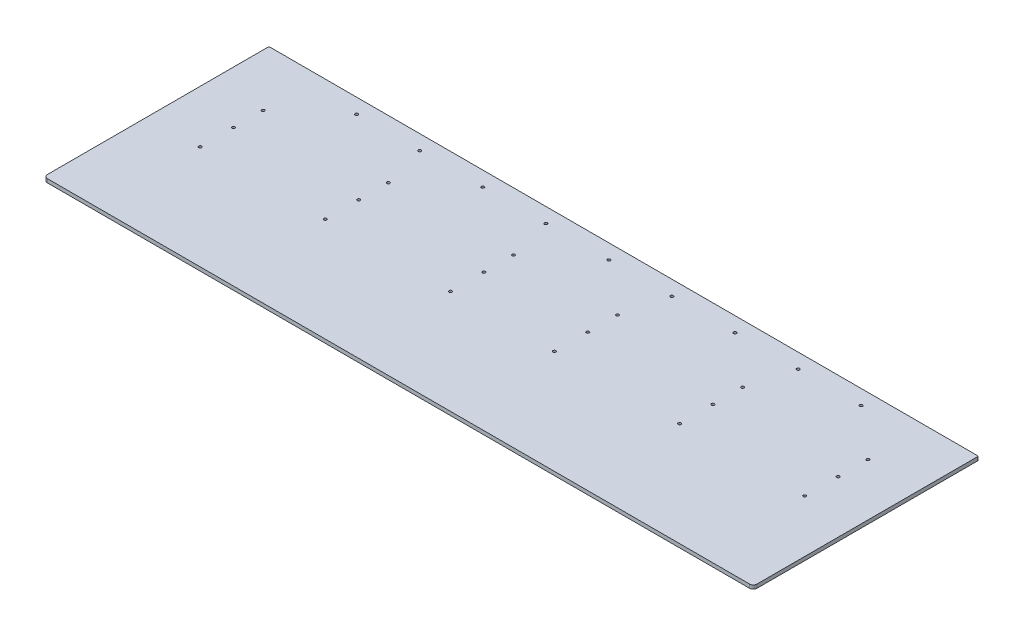
SolidWorks part; units mm, degrees
material "PC High Viscosity"
ref_plane "Front Plane" through (0, 0, 0) normal (0, 0, 1) x (1, 0, 0)
ref_plane "Top Plane" through (0, 0, 0) normal (0, 1, 0) x (1, 0, 0)
ref_plane "Right Plane" through (0, 0, 0) normal (1, 0, 0) x (0, 0, -1)
sketch "Sketch1" plane through (0, 0, 0) normal (0, 1, 0) x (1, 0, 0)
  line L1 (0, 0) -> (1219.2, 0)
  line L2 (0, 0) -> (0, 366.776)
  line L3 (0, 366.776) -> (1219.2, 366.776)
  line L4 (1219.2, 0) -> (1219.2, 366.776)
  dimension "D1" = 366.776
  dimension "D2" = 1219.2
extrude "Boss-Extrude1" add sketch "Sketch1" along normal blind 6.35
hole_wizard "#10 (0.1935) Diameter Hole1" positions "Sketch2" profile "Sketch3" hole size "#10" standard "ANSI Inch" end condition through all
sketch "Sketch2" plane through (0, 6.35, 0) normal (0, 1, 0) x (1, 0, 0)
  line L0 (1219.2, 366.776) -> (0, 366.776) construction
  line L1 (609.6, 0) -> (609.6, 366.776) construction
  line L2 (0, 0) -> (1219.2, 0) construction
  line L3 (0, 366.776) -> (0, 0) construction
  point P0 (177.8, 335.026)
  point P7 (285.75, 335.026)
  point P8 (393.7, 335.026)
  point P9 (501.65, 335.026)
  point P10 (609.6, 335.026)
  point P11 (717.55, 335.026)
  point P23 (139.7, 289.7505)
  point P29 (609.6, 289.7505)
  point P30 (1079.5, 289.7505)
  point P31 (609.6, 238.9505)
  point P32 (1079.5, 238.9505)
  point P33 (609.6, 188.1505)
  point P34 (1079.5, 188.1505)
  point P35 (609.6, 137.3505)
  point P36 (1079.5, 137.3505)
  point P37 (139.7, 238.9505)
  point P38 (139.7, 188.1505)
  point P39 (139.7, 137.3505)
  point P58 (825.5, 335.026)
  point P59 (933.45, 335.026)
  point P60 (1041.4, 335.026)
  dimension "D2" = 31.75
  dimension "D3" = 107.95
  dimension "D6" = 50.8
  dimension "D7" = 137.3505
  dimension "D8" = 139.7
  dimension "D1" = 9
  dimension "D4" = 3
  dimension "D5" = 4
sketch "Sketch3" plane through (177.8, 6.35, -335.026) normal (1, 0, 0) x (0, 0, 1)
  line L0 (0, 0) -> (0, 6.35)
  line L1 (0, 6.35) -> (2.4574, 6.35)
  line L2 (2.4574, 6.35) -> (2.4574, 0)
  line L5 (2.4574, 0) -> (0, 0)
  line L11 (0, -6.35) -> (0, 107.95) construction
  dimension "Thru Hole Dia." = 4.9149
  dimension "Thru Hole Depth" = 6.35
sketch "Sketch4" plane through (0, 6.35, 0) normal (0, 1, 0) x (1, 0, 0)
  line L0 (1219.2, 0) -> (1219.2, 366.776) construction
  line L1 (0, 366.776) -> (1219.2, 366.776)
  line L2 (0, 366.776) -> (0, 360.426)
  line L3 (0, 360.426) -> (1219.2, 360.426)
  line L4 (1219.2, 366.776) -> (1219.2, 360.426)
  dimension "D1" = 6.35
extrude "Cut-Extrude1" cut sketch "Sketch4" against normal through all
sketch "Sketch5" plane through (0, 6.35, 0) normal (0, 1, 0) x (1, 0, 0)
  line L0 (609.6, 360.426) -> (609.6, 0) construction
  line L1 (0, 360.426) -> (1219.2, 360.426) construction
  line L2 (0, 0) -> (1219.2, 0) construction
  line L3 (1216.8188, 360.426) -> (1216.8188, 0)
  line L4 (0, 360.426) -> (2.3812, 360.426)
  line L5 (0, 360.426) -> (0, 0)
  line L6 (0, 0) -> (2.3813, 0)
  line L7 (2.3812, 360.426) -> (2.3813, 0)
  line L8 (1219.2, 0) -> (1216.8188, 0)
  line L9 (1219.2, 360.426) -> (1219.2, 0)
  line L10 (1219.2, 360.426) -> (1216.8188, 360.426)
  dimension "D1" = 2.3813
extrude "Cut-Extrude2" cut sketch "Sketch5" against normal through all
fillet "Fillet1" radius 1.27 2 edges at (1216.8187, 3.175, -360.426) (2.3812, 3.175, -360.426)
sketch "Sketch6" plane through (0, 6.35, 0) normal (0, 1, 0) x (1, 0, 0)
  circle A0 centre (1079.5, 137.3505) radius 2.4575 construction
  circle A1 centre (1079.5, 188.1505) radius 2.4575 construction
  circle A2 centre (1079.5, 238.9505) radius 2.4575 construction
  circle A3 centre (1079.5, 289.7505) radius 2.4575 construction
  circle A4 centre (609.6, 137.3505) radius 2.4574 construction
  circle A5 centre (609.6, 188.1505) radius 2.4574 construction
  circle A6 centre (609.6, 238.9505) radius 2.4574 construction
  circle A7 centre (609.6, 289.7505) radius 2.4574 construction
  circle A8 centre (139.7, 137.3505) radius 2.4574 construction
  circle A9 centre (139.7, 188.1505) radius 2.4574 construction
  circle A10 centre (139.7, 238.9505) radius 2.4574 construction
  circle A11 centre (139.7, 289.7505) radius 2.4574 construction
  circle A12 centre (1079.5, 137.3505) radius 2.4575
  circle A13 centre (1079.5, 188.1505) radius 2.4575
  circle A14 centre (1079.5, 238.9505) radius 2.4575
  circle A15 centre (1079.5, 289.7505) radius 2.4575
  circle A16 centre (609.6, 137.3505) radius 2.4575
  circle A17 centre (609.6, 188.1505) radius 2.4575
  circle A18 centre (609.6, 238.9505) radius 2.4575
  circle A19 centre (609.6, 289.7505) radius 2.4575
  circle A20 centre (139.7, 137.3505) radius 2.4575
  circle A21 centre (139.7, 188.1505) radius 2.4575
  circle A22 centre (139.7, 238.9505) radius 2.4575
  circle A23 centre (139.7, 289.7505) radius 2.4574
extrude "Boss-Extrude2" add sketch "Sketch6" against normal up to surface (6.35 mm away) up to face at (609.6, 0, -239.9483)
hole_wizard "#10 (0.1935) Diameter Hole2" positions "Sketch7" profile "Sketch8" hole size "#10" standard "ANSI Inch" end condition through all
sketch "Sketch7" plane through (0, 6.35, 0) normal (0, 1, 0) x (1, 0, 0)
  line L0 (609.6, 0) -> (609.6, 360.426) construction
  line L1 (2.3813, 0) -> (1216.8188, 0) construction
  line L2 (3.6512, 360.426) -> (1215.5487, 360.426) construction
  line L3 (306.3875, 0) -> (306.3875, 360.426) construction
  point P0 (92.075, 260.7564)
  point P2 (92.075, 209.9564)
  point P4 (92.075, 152.8064)
  point P6 (306.3875, 260.7564)
  point P8 (306.3875, 209.9564)
  point P10 (306.3875, 152.8064)
  point P36 (520.7, 152.8064)
  point P37 (520.7, 209.9564)
  point P38 (520.7, 260.7564)
  point P39 (698.5, 260.7564)
  point P40 (698.5, 209.9564)
  point P41 (698.5, 152.8064)
  point P42 (912.8125, 152.8064)
  point P43 (912.8125, 209.9564)
  point P44 (912.8125, 260.7564)
  point P45 (1127.125, 152.8064)
  point P46 (1127.125, 209.9564)
  point P47 (1127.125, 260.7564)
  dimension "D1" = 152.8064
  dimension "D2" = 57.15
  dimension "D3" = 50.8
  dimension "D4" = 303.2125
  dimension "D5" = 88.9
sketch "Sketch8" plane through (92.075, 6.35, -260.7564) normal (1, 0, 0) x (0, 0, 1)
  line L0 (0, 0) -> (0, 6.35)
  line L1 (0, 6.35) -> (2.4574, 6.35)
  line L2 (2.4574, 6.35) -> (2.4574, 0)
  line L5 (2.4574, 0) -> (0, 0)
  line L11 (0, -6.35) -> (0, 107.95) construction
  dimension "Thru Hole Dia." = 4.9149
  dimension "Thru Hole Depth" = 6.35
sketch "Sketch9" plane through (0, 6.35, 0) normal (0, 1, 0) x (1, 0, 0)
  line L1 (2.3813, 0) -> (1216.8188, 0)
  line L2 (2.3813, 0) -> (2.3813, -24.9936)
  line L3 (2.3813, -24.9936) -> (1216.8188, -24.9936)
  line L4 (1216.8188, 0) -> (1216.8188, -24.9936)
  dimension "D1" = 24.9936
extrude "Boss-Extrude3" add sketch "Sketch9" against normal up to surface (6.35 mm away) up to face at (92.075, 0, -258.299)
fillet "Fillet2" radius 6.35 2 edges at (1216.8188, 3.175, 24.9936) (2.3813, 3.175, 24.9936)
